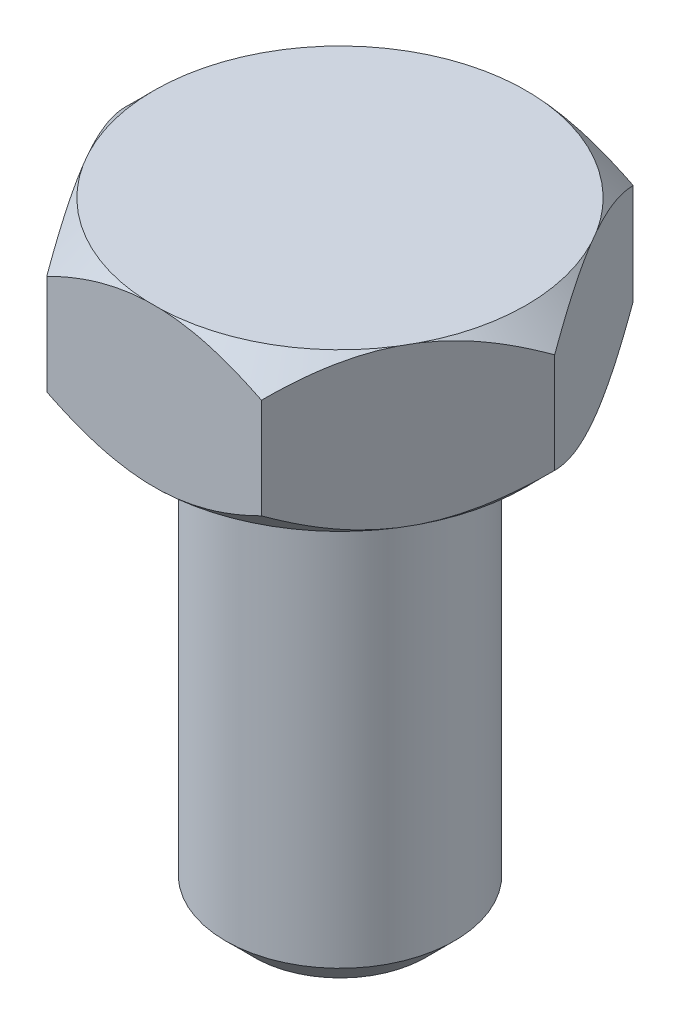
SolidWorks part; units mm, degrees
ref_plane "Спереди" through (0, 0, 0) normal (0, 0, 1) x (1, 0, 0)
ref_plane "Сверху" through (0, 0, 0) normal (0, 1, 0) x (1, 0, 0)
ref_plane "Справа" through (0, 0, 0) normal (1, 0, 0) x (0, 0, -1)
sketch "Эскиз1" plane through (0, 0, 0) normal (0, 1, 0) x (1, 0, 0)
  line L0 (-3.7528, 6.5) -> (3.7528, 6.5)
  line L1 (3.7528, 6.5) -> (7.5056, 0)
  line L2 (7.5056, 0) -> (3.7528, -6.5)
  line L3 (3.7528, -6.5) -> (-3.7528, -6.5)
  line L4 (-3.7528, -6.5) -> (-7.5056, 0)
  line L5 (-7.5056, 0) -> (-3.7528, 6.5)
  dimension "D5" = 6.5
  dimension "D2" = 120
  dimension "D3" = 120
  dimension "D4" = 120
  dimension "D6" = 6.5
  dimension "D7" = 6.5
  dimension "D8" = 6.5
  dimension "D9" = 6.5
  dimension "D10" = 120
  dimension "D11" = 6.5
extrude "Вытянуть1" add sketch "Эскиз1" against normal blind 5.5
sketch "Эскиз5" plane through (0, -5.5, 0) normal (0, -1, 0) x (1, 0, 0)
  circle A0 centre (0, 0) radius 4
  dimension "D1" = 8
extrude "Вытянуть2" add sketch "Эскиз5" along normal blind 16
chamfer "Фаска1" distance 1 angle 45 1 edges at (0, -21.5, -4)
ref_axis "Ось1" through (0, -5.5, 0) along (0, -1, 0)
ref_plane "Плоскость1" through (0, 0, 0) normal (0, 0, 1) x (1, 0, 0)
sketch "Эскиз4" plane through (0, 0, 0) normal (0, 0, 1) x (1, 0, 0)
  line L0 (-7.5056, -1) -> (-6.5056, 0)
  line L1 (-7.5056, -5.5) -> (-7.5056, 0) construction
  line L2 (-7.5056, 0) -> (-3.7528, 0) construction
  line L3 (-6.5056, 0) -> (-7.5056, 0)
  line L4 (-7.5056, 0) -> (-7.5056, -1)
  line L5 (-7.5056, -4.5) -> (-6.5056, -5.5)
  line L6 (-7.5056, -5.5) -> (-3.7528, -5.5) construction
  line L7 (-6.5056, -5.5) -> (-7.5056, -5.5)
  line L8 (-7.5056, -5.5) -> (-7.5056, -4.5)
  dimension "D1" = 1
  dimension "D2" = 1
  dimension "D3" = 1
  dimension "D4" = 1
revolve "Вырез-Повернуть1" cut sketch "Эскиз4" angle 360 about axis through (0, -5.5, 0) along (0, -1, 0)
